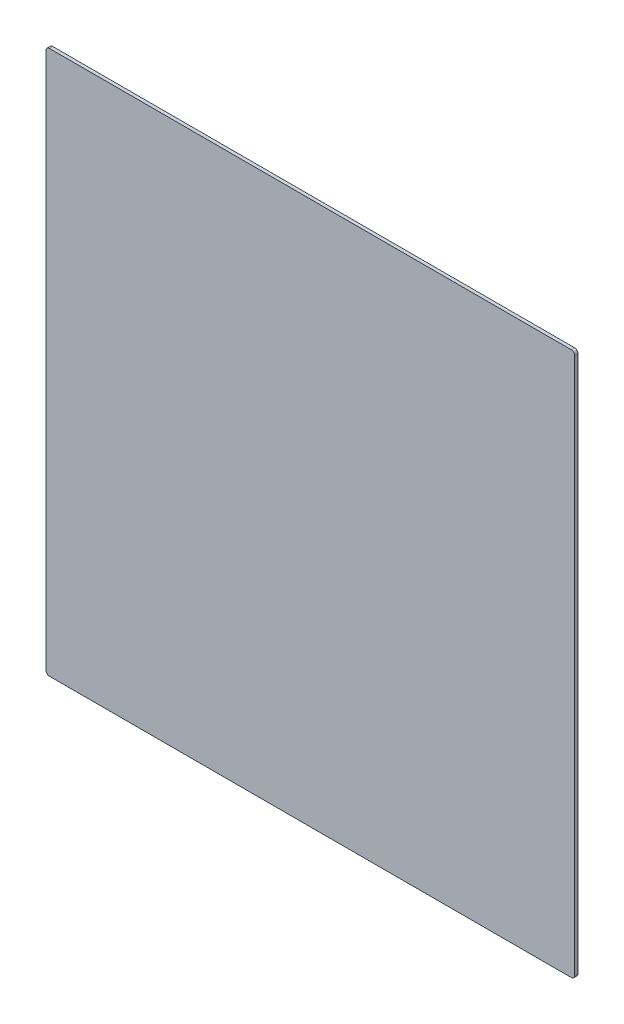
SolidWorks part; units mm, degrees
material "Acrylic (Medium-high impact)"
ref_plane "Front Plane" through (0, 0, 0) normal (0, 0, 1) x (1, 0, 0)
ref_plane "Top Plane" through (0, 0, 0) normal (0, 1, 0) x (1, 0, 0)
ref_plane "Right Plane" through (0, 0, 0) normal (1, 0, 0) x (0, 0, -1)
sketch "Sketch1" plane through (0, 0, 0) normal (0, 0, 1) x (1, 0, 0)
  line L1 (-247.65, -257.9687) -> (247.65, -257.9687)
  line L2 (-250.825, -254.7937) -> (-250.825, 254.7937)
  line L3 (-247.65, 257.9687) -> (247.65, 257.9687)
  line L4 (250.825, -254.7937) -> (250.825, 254.7937)
  line L5 (-250.825, -257.9687) -> (250.825, 257.9687) construction
  line L6 (-250.825, 257.9687) -> (250.825, -257.9687) construction
  arc A0 (-247.65, -257.9687) -> (-250.825, -254.7937) centre (-247.65, -254.7937) cw
  arc A1 (247.65, -257.9687) -> (250.825, -254.7937) centre (247.65, -254.7937) ccw
  arc A2 (247.65, 257.9687) -> (250.825, 254.7937) centre (247.65, 254.7937) cw
  arc A3 (-250.825, 254.7937) -> (-247.65, 257.9687) centre (-247.65, 254.7937) cw
  point P0 (0, 0)
  dimension "D3" = 3.175
  dimension "D1" = 515.9375
  dimension "D2" = 501.65
extrude "Boss-Extrude1" add sketch "Sketch1" along normal blind 3.175
